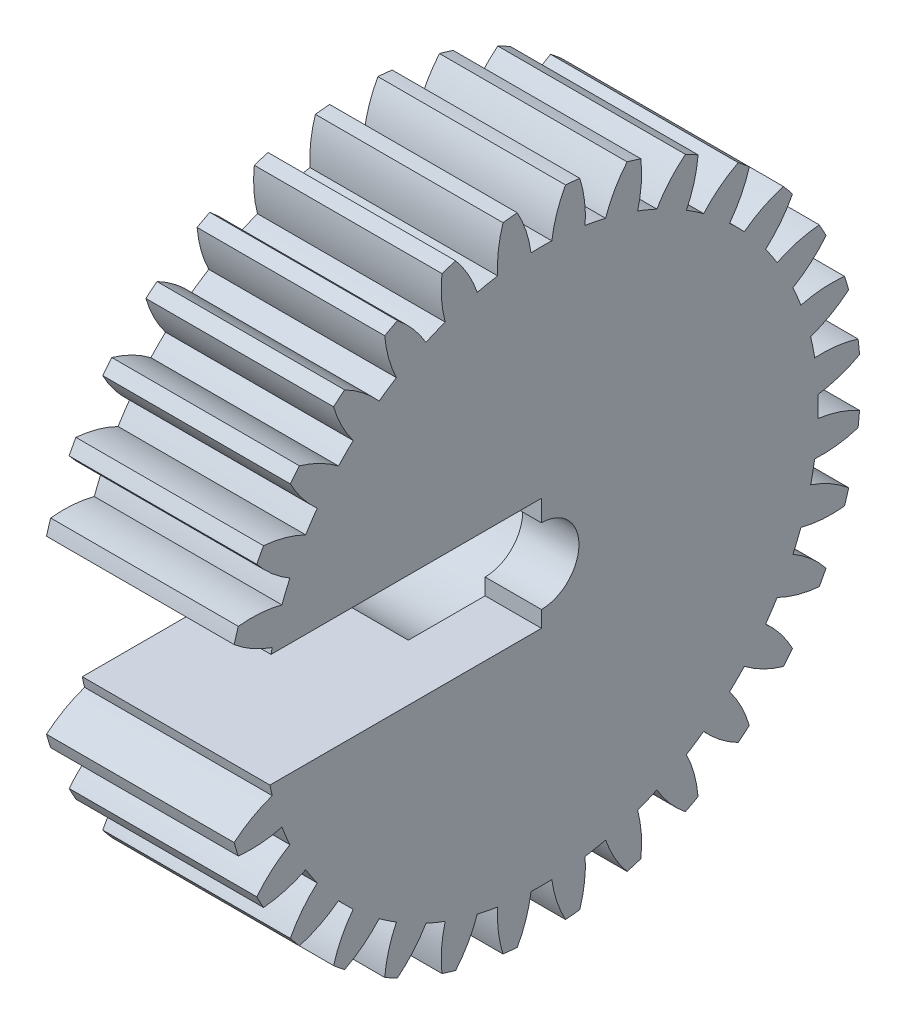
SolidWorks part; units mm, degrees
ref_plane "Plane1" through (0, 0, 0) normal (0, 0, 1) x (1, 0, 0)
ref_plane "Plane2" through (0, 0, 0) normal (0, 1, 0) x (1, 0, 0)
ref_plane "Plane3" through (0, 0, 0) normal (1, 0, 0) x (0, 0, -1)
other "Configuration Table"
sketch "HoldingSke" plane through (0, 0, 0) normal (0, 1, 0) x (1, 0, 0)
  line L0 (0, 0) -> (1.6961, -1.0598)
  line L1 (-15, 0) -> (100, 0) construction
  line L2 (0, 0) -> (-2.1039, 2.3779)
  line L3 (0, 0) -> (-11.863, 4.5341)
  line L4 (0, 0) -> (7.3237, 4.5764)
  line L5 (0, 0) -> (-46.8476, -17.4728)
  line L6 (0, 0) -> (-4.1448, -2.7965)
  line L7 (-2.1039, 2.3779) -> (8.6586, 51.2059)
  line L8 (-76.2, 54.61) -> (-75.9, 54.61)
  line L9 (-67.7845, 28.3722) -> (-49.3413, 33.142)
  line L10 (-76.2, 71.12) -> (104.1128, 71.12)
  line L11 (0, 0) -> (-5, 0)
  line L12 (-76.2, 101.6) -> (-76.181, 101.6)
  line L13 (24.9733, 27.94) -> (52.9518, 28.4284)
  line L14 (24.9733, 27.94) -> (24.9743, 27.94)
  line L15 (24.9733, 27.94) -> (100.4006, 29.5858)
  line L16 (-63.627, -0.5) -> (-12.827, -0.5)
  circle A0 centre (0, 0) radius 1
  circle A1 centre (0, 0) radius 7.374
  circle A2 centre (0, 0) radius 37.5
  circle A3 centre (0, 0) radius 1
  dimension "MHD" = 14.748
  dimension "Hub_dia" = 75
  dimension "Bore" = 2
  dimension "MBD" = 2
  dimension "Num_teeth" = 32
  dimension "Pitch" = 2
  dimension "Overall_len" = 50
  dimension "Show_teeth" = 32
  dimension "Thickness" = 5
  dimension "OAL" = 50.0001
  dimension "T_dim" = 0.3
  dimension "Ap" = 14.5
  dimension "H" = 19.05
  dimension "Pitch_radius" = 180.3128
  dimension "Width" = 5
  dimension "Backlash" = 0.019
  dimension "Addendum_fac" = 1
  dimension "Dedendum_fac" = 1.25
  dimension "Clearance_fac" = 0.25
  dimension "Dedendum_add" = 0.001
  dimension "Module" = 0.5
sketch "BasProSke" plane through (0, 0, 0) normal (0, 1, 0) x (1, 0, 0)
  line L0 (-10, 0) -> (60, 0) construction
  line L1 (0, 0) -> (0, 8.5)
  line L2 (0, 0) -> (5, 0)
  line L3 (5, 0) -> (5, 8.5)
  line L4 (5, 8.5) -> (0, 8.5)
  dimension "Thickness" = 5
  dimension "Diameter" = 17
revolve "Base-Revolve" add sketch "BasProSke" angle 360 about L0
sketch "TooCutSke" plane through (0, 0, 0) normal (1, 0, 0) x (0, 0, -1)
  line L1 (0, 0) -> (0, 107) construction
  line L2 (0, 0) -> (-0.4258, 7.9887) construction
  line L3 (0, 0) -> (-1.5667, 15.9069) construction
  line L4 (-0.4258, 7.9887) -> (-0.7833, 7.9534) construction
  arc A0 (0.277, 7.3688) -> (-0.277, 7.3688) centre (0, 0) ccw
  arc A1 (0.6561, 8.5001) -> (-0.6561, 8.5001) centre (0, 0) ccw
  circle A2 centre (0, 0) radius 8 construction
  circle A3 centre (0, 0) radius 7.7452 construction
  arc A4 (-0.277, 7.3688) -> (-0.6561, 8.5001) centre (-3.4475, 6.9356) ccw
  arc A5 (0.6561, 8.5001) -> (0.277, 7.3688) centre (3.4475, 6.9356) ccw
  dimension "Root_dia" = 14.748
  dimension "Overcut_dia" = 17.0508
  dimension "Pitch_dia" = 16
  dimension "Base_dia" = 15.4904
  dimension "Flank_rad" = 3.2
  dimension "Half_ang" = 5.625
  dimension "Half_CT" = 0.3593
extrude "ToothCut" cut sketch "TooCutSke" along normal through all
fillet "Breaks" [suppressed] radius 0.01
fillet "RootFillets" [suppressed] radius 0.126
pattern_circular "TeethCuts" count 32 every 11.25 about axis through (-10, 0, 0) along (1, 0, 0) of "ToothCut", "RootFillets", "Breaks"
sketch "HubNeaOneSke" plane through (0, 0, 0) normal (-1, 0, 0) x (0, 0, 1)
  circle A0 centre (0, 0) radius 7.374
  dimension "Diameter" = 14.748
extrude "HubNearOne" [suppressed] add sketch "HubNeaOneSke" along normal blind 45.0001
sketch "HubNeaBotSke" plane through (0, 0, 0) normal (-1, 0, 0) x (0, 0, 1)
  circle A0 centre (0, 0) radius 7.374
  dimension "Diameter" = 14.748
extrude "HubNearBoth" [suppressed] add sketch "HubNeaBotSke" along normal blind 22.5
ref_plane "FarPln" through (5, 0, 0) normal (1, 0, 0) x (0, 0, -1)
sketch "HubFarSke" plane through (5, 0, 0) normal (1, 0, 0) x (0, 0, -1)
  circle A0 centre (0, 0) radius 7.374
  dimension "Diameter" = 14.748
extrude "HubFar" [suppressed] add sketch "HubFarSke" along normal blind 22.5
sketch "BorSke" plane through (0, 0, 0) normal (1, 0, 0) x (0, 0, -1)
  circle A0 centre (0, 0) radius 1
  dimension "Diameter" = 2
extrude "Bore" cut sketch "BorSke" along normal mid plane 100.0001
sketch "KeySke" plane through (0, 0, 0) normal (1, 0, 0) x (0, 0, -1)
  line L0 (-0.4, 0) -> (-0.4, 1.3)
  line L1 (-0.4, 1.3) -> (0.4, 1.3)
  line L2 (0.4, 1.3) -> (0.4, 0)
  line L3 (0, 0) -> (0, 34) construction
  line L4 (-0.4, 0) -> (0.4, 0)
  dimension "Offset" = 1.3
  dimension "Width" = 0.8
extrude "Keyway" [suppressed] cut sketch "KeySke" along normal mid plane 100.0001
pattern_circular "Keyway2" [suppressed] count 2 every 90 about axis through (-10, 0, 0) along (1, 0, 0)
sketch "Sketch1" plane through (5, 0, 0) normal (1, 0, 0) x (0, 0, -1)
  line L4 (0, 1.5656) -> (0, -1.4344)
  line L5 (0, -1.4344) -> (-10, -1.4344)
  line L6 (-10, -1.4344) -> (-10, 1.5656)
  line L7 (-10, 1.5656) -> (0, 1.5656)
  dimension "D1" = 10
  dimension "D2" = 10
  dimension "D3" = 3
  dimension "D4" = 3
extrude "Cut-Extrude1" cut sketch "Sketch1" against normal through all both
ref_plane "Plane5" through (0, 0.0656, 0) normal (0, 1, 0) x (1, 0, 0)
sketch "Sketch2" plane through (0, 0, 0) normal (-1, 0, 0) x (0, 0, 1)
  circle A0 centre (0, 0) radius 2.5
extrude "Cut-Extrude2" cut sketch "Sketch2" against normal blind 3.5
equation "' \"Module@HoldingSke\" = 6.35"
equation "' \"Num_teeth@HoldingSke\" = 12"
equation "' \"Ap@HoldingSke\" =  20"
equation "' \"Ap@HoldingSke\" = 20"
equation "' \"Width@HoldingSke\" = 0.5 * 25.4"
equation "' \"Hub_dia@HoldingSke\"= 1 * 25.4"
equation "' \"Hub_dia@HoldingSke\" = 1 * 25.4"
equation "' \"Overall_len@HoldingSke\" = 1.0 * 25.4"
equation "' \"Bore@HoldingSke\" = 0.75 * 25.4"
equation "' \"T_dim@HoldingSke\" = 0.1 * 25.4"
equation "' \"Width@KeySke\" = 0.25 * 25.4"
equation "' \"Show_teeth@HoldingSke\" = 13"
equation "' \"Backlash@HoldingSke\" = 0.009 * 25.4"
equation "' \"Addendum_fac@HoldingSke\" = 1.0"
equation "' \"Dedendum_fac@HoldingSke\" = 1.25"
equation "' \"Dedendum_add@HoldingSke\" = 0.00005 * 25.4"
equation "' \"Clearance_fac@HoldingSke\" = 0.25"
equation "\"Pitch@HoldingSke\" = 1 / \"Module@HoldingSke\""
equation "\"Overcut_dia@TooCutSke\" = (\"Num_teeth@HoldingSke\" + 2 * \"Addendum_fac@HoldingSke\") / \"Pitch@HoldingSke\" + 0.002 * 25.4"
equation "\"Pitch_dia@TooCutSke\" = \"Num_teeth@HoldingSke\" / \"Pitch@HoldingSke\""
equation "\"Base_dia@TooCutSke\" = \"Num_teeth@HoldingSke\" / \"Pitch@HoldingSke\" * cos((\"Ap@HoldingSke\"  * 3.14159265 / 180))"
equation "\"Root_dia@TooCutSke\" = (\"Num_teeth@HoldingSke\" + 2) / \"Pitch@HoldingSke\" - 2 * (\"Addendum_fac@HoldingSke\" + \"Dedendum_fac@HoldingSke\") / \"Pitch@HoldingSke\" - \"Dedendum_add@HoldingSke\" * 2"
equation "\"Half_ang@TooCutSke\" = 180 / \"Num_teeth@HoldingSke\""
equation "\"Half_CT@TooCutSke\" = \"Num_teeth@HoldingSke\" / \"Pitch@HoldingSke\" * sin((3.14159265 / 2 / \"Num_teeth@HoldingSke\")) / 2 - 7 * \"Backlash@HoldingSke\" / 4"
equation "\"Flank_rad@TooCutSke\" = \"Num_teeth@HoldingSke\" / \"Pitch@HoldingSke\" / 5"
equation "\"Radius@RootFillets\" = \"Clearance_fac@HoldingSke\" / \"Pitch@HoldingSke\" + \"Dedendum_add@HoldingSke\""
equation "\"Break_rad@Breaks\" = 0.02 / \"Pitch@HoldingSke\""
equation "\"Thickness@HoldingSke\" = \"Width@HoldingSke\""
equation "\"OAL@HoldingSke\" = \"Thickness@HoldingSke\""
equation "\"MHD@HoldingSke\" = (\"Num_teeth@HoldingSke\" + 2) / \"Pitch@HoldingSke\" - 2 * (\"Addendum_fac@HoldingSke\" + \"Dedendum_fac@HoldingSke\")  / \"Pitch@HoldingSke\" - \"Dedendum_add@HoldingSke\" * 2"
equation "\"MBD@HoldingSke\" = (\"Num_teeth@HoldingSke\" + 2) / \"Pitch@HoldingSke\" - 2 * (\"Addendum_fac@HoldingSke\" + \"Dedendum_fac@HoldingSke\")  / \"Pitch@HoldingSke\" - \"Dedendum_add@HoldingSke\" * 2 - 0.002 * 25.4"
equation "\"MHD@HoldingSke\" = ((sgn( \"MHD@HoldingSke\" - \"Hub_dia@HoldingSke\" )-1)*( \"MHD@HoldingSke\" - \"Hub_dia@HoldingSke\" ))/-2+ \"Hub_dia@HoldingSke\""
equation "\"MBD@HoldingSke\" = ((sgn( \"MBD@HoldingSke\" - \"Bore@HoldingSke\" )-1)*( \"MBD@HoldingSke\" - \"Bore@HoldingSke\" ))/-2+ \"Bore@HoldingSke\""
equation "\"OAL@HoldingSke\" = ((sgn( \"OAL@HoldingSke\" - \"Overall_len@HoldingSke\" )+1)*( \"OAL@HoldingSke\" - \"Overall_len@HoldingSke\" ))/2 + \"Overall_len@HoldingSke\" + 0.000002 * 25.4"
equation "\"Num_teeth@TeethCuts\" = int( \"Show_teeth@HoldingSke\" ) + 1"
equation "\"Num_teeth@TeethCuts\" = ((sgn( \"Num_teeth@TeethCuts\" - \"Num_teeth@HoldingSke\" )-1)*( \"Num_teeth@TeethCuts\" - \"Num_teeth@HoldingSke\" ))/-2+ \"Num_teeth@HoldingSke\""
equation "\"Num_teeth@TeethCuts\" = ((sgn( \"Num_teeth@TeethCuts\" - 2.0)+1)*( \"Num_teeth@TeethCuts\" - 2.0))/2 +2.0"
equation "\"Angle@TeethCuts\" = 360.0 / \"Num_teeth@HoldingSke\""
equation "\"Diameter@BasProSke\" = (\"Num_teeth@HoldingSke\" + 2 * \"Addendum_fac@HoldingSke\") / \"Pitch@HoldingSke\""
equation "\"Thickness@BasProSke\"  = \"Thickness@HoldingSke\""
equation "' \"Fillet_rad@BasProSke\" =  \"Thickness@HoldingSke\" * 0.05"
equation "' \"Fillet_rad@BasProSke\" = \"Thickness@HoldingSke\" * 0.05"
equation "\"MHD@HoldingSke\" = ((sgn( \"MHD@HoldingSke\" - \"Root_dia@TooCutSke\" )-1)*( \"MHD@HoldingSke\" - \"Root_dia@TooCutSke\" ))/-2+ \"Root_dia@TooCutSke\""
equation "\"Diameter@HubNeaOneSke\" = \"MHD@HoldingSke\""
equation "\"Length@HubNearOne\" = \"OAL@HoldingSke\" - \"Thickness@BasProSke\""
equation "\"Diameter@HubNeaBotSke\" = \"MHD@HoldingSke\""
equation "\"Length@HubNearBoth\" = ( \"OAL@HoldingSke\" - \"Thickness@BasProSke\" ) / 2.0"
equation "\"Thickness@FarPln\" = \"Thickness@BasProSke\""
equation "\"Diameter@HubFarSke\" = \"MHD@HoldingSke\""
equation "\"Length@HubFar\" = ( \"OAL@HoldingSke\" - \"Thickness@BasProSke\" ) / 2.0"
equation "\"Diameter@BorSke\" = \"MBD@HoldingSke\""
equation "\"D1@Bore\" = \"OAL@HoldingSke\" * 2.0"
equation "\"D1@Keyway\" = \"OAL@HoldingSke\" * 2.0"
equation "\"Offset@KeySke\" = \"T_dim@HoldingSke\" + \"MBD@HoldingSke\" / 2.0"
